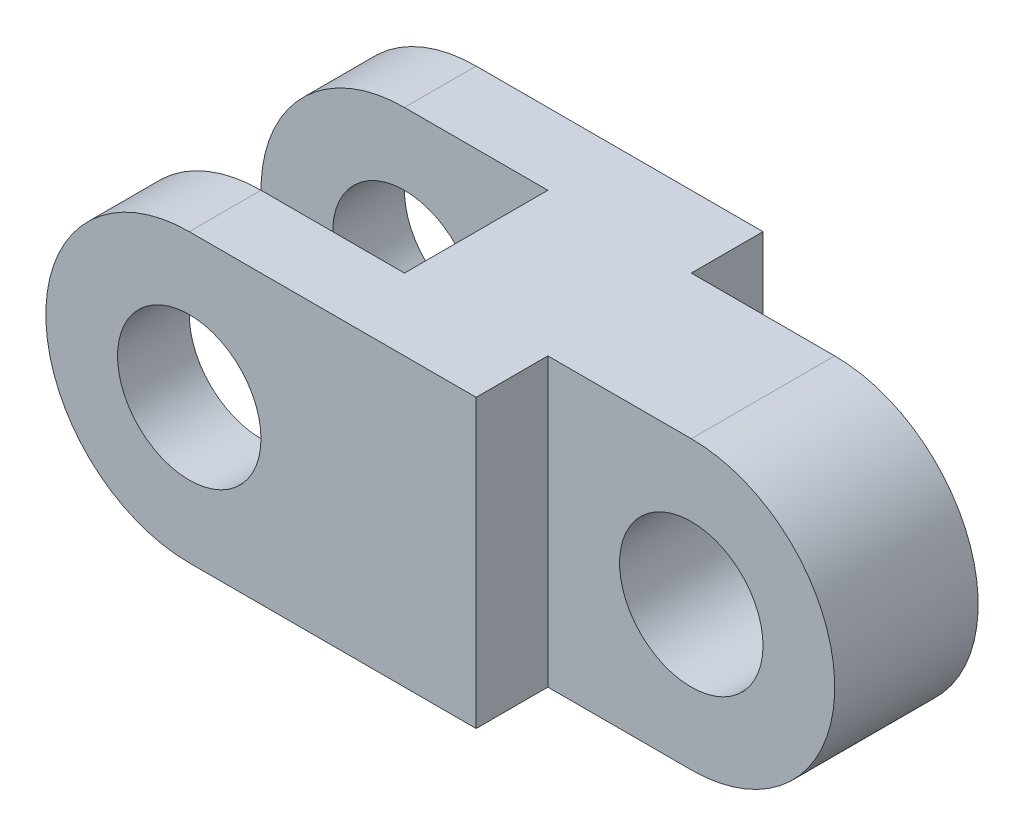
SolidWorks part; units mm, degrees
ref_plane "Front Plane" through (0, 0, 0) normal (0, 0, 1) x (1, 0, 0)
ref_plane "Top Plane" through (0, 0, 0) normal (0, 1, 0) x (1, 0, 0)
ref_plane "Right Plane" through (0, 0, 0) normal (1, 0, 0) x (0, 0, -1)
sketch "Sketch2" plane through (0, 0, 0) normal (0, 0, 1) x (1, 0, 0)
  line L1 (-75, -50) -> (75, -50)
  line L2 (-75, -50) -> (-75, 50)
  line L3 (-75, 50) -> (75, 50)
  line L4 (75, -50) -> (75, 50)
  line L5 (-75, -50) -> (75, 50) construction
  line L6 (-75, 50) -> (75, -50) construction
  circle A2 centre (-75, 0) radius 50
  circle A3 centre (75, 0) radius 50
  point P0 (0, 0)
  dimension "D1" = 150
  dimension "D2" = 100
extrude "Boss-Extrude1" add sketch "Sketch2" along normal mid plane 100 contours L2 A2 | L2 A2 | A3 L3 A2 L1 | L4 A3 | L4 A3
sketch "Sketch4" plane through (0, 0, 0) normal (0, 0, 1) x (1, 0, 0)
  line L0 (-75, -50) -> (-75, 50)
  line L2 (-75, -50) -> (75, -50)
  line L3 (75, 50) -> (-75, 50)
  line L4 (-75, -50) -> (75, -50)
  line L5 (75, 50) -> (-75, 50)
  arc A2 (-75, 50) -> (-75, -50) centre (-75, 0) ccw
  arc A3 (75, -50) -> (75, 50) centre (75, 0) ccw
  arc A4 (-75, 50) -> (-75, -50) centre (-75, 0) ccw
  arc A5 (75, -50) -> (75, 50) centre (75, 0) ccw
  point P8 (-75, 0)
  dimension "D1" = 0
extrude "Cut-Extrude1" cut sketch "Sketch4" against normal mid plane 50 contours L0 A4
sketch "Sketch7" plane through (0, 50, 0) normal (0, 1, 0) x (1, 0, 0)
  line L0 (-75, 25) -> (-25, 25)
  line L1 (-25, 25) -> (-25, -25)
  line L2 (-25, -25) -> (-75, -25)
  line L6 (75, 50) -> (-75, 50)
  line L7 (-75, 50) -> (-75, 25)
  line L8 (-75, 25) -> (-75, -25)
  line L9 (-75, -25) -> (-75, -50)
  line L10 (-75, -50) -> (75, -50)
  line L11 (75, -50) -> (75, 50)
  line L12 (75, 50) -> (-75, 50)
  line L13 (-75, 50) -> (-75, 25)
  line L14 (-75, 25) -> (-75, -25)
  line L15 (-75, -25) -> (-75, -50)
  line L16 (-75, -50) -> (75, -50)
  line L17 (75, -50) -> (75, 50)
  line M9 (-75, 25) -> (-75, -25)
  dimension "D2" = 25
  dimension "D1" = 0
extrude "Cut-Extrude2" cut sketch "Sketch7" against normal through all contours L2 L1 L0 M9
sketch "Sketch8" plane through (0, 0, 50) normal (0, 0, 1) x (1, 0, 0)
  line L2 (-75, -50) -> (75, -50)
  line L3 (75, 50) -> (-75, 50)
  line L4 (-75, -50) -> (75, -50)
  line L5 (75, 50) -> (-75, 50)
  circle A0 centre (-75, 0) radius 25
  arc A2 (-75, 50) -> (-75, -50) centre (-75, 0) ccw
  arc A3 (75, -50) -> (75, 50) centre (75, 0) ccw
  arc A4 (-75, 50) -> (-75, -50) centre (-75, 0) ccw
  arc A5 (75, -50) -> (75, 50) centre (75, 0) ccw
  dimension "D2" = 50
  dimension "D1" = 0
extrude "Cut-Extrude3" cut sketch "Sketch8" against normal through all both and the other way through all contours A0
sketch "Sketch9" plane through (0, 0, 50) normal (0, 0, 1) x (1, 0, 0)
  line L2 (-75, -50) -> (75, -50)
  line L3 (75, 50) -> (-75, 50)
  line L4 (-75, -50) -> (75, -50)
  line L5 (75, 50) -> (-75, 50)
  circle A0 centre (75, 0) radius 25
  arc A2 (-75, 50) -> (-75, -50) centre (-75, 0) ccw
  arc A3 (75, -50) -> (75, 50) centre (75, 0) ccw
  arc A4 (-75, 50) -> (-75, -50) centre (-75, 0) ccw
  arc A5 (75, -50) -> (75, 50) centre (75, 0) ccw
  dimension "D2" = 50
  dimension "D1" = 0
extrude "Cut-Extrude4" cut sketch "Sketch9" against normal through all both contours A0
sketch "Sketch13" plane through (0, 0, 50) normal (0, 0, 1) x (1, 0, 0)
  line L0 (25, 50) -> (25, -50)
  line L1 (-75, 50) -> (75, 50) construction
  line L2 (-75, -50) -> (75, -50) construction
  dimension "D1" = 25
sketch "Sketch15" plane through (0, 0, 50) normal (0, 0, 1) x (1, 0, 0)
  line L0 (25, 50) -> (25, -50) construction
  line L1 (25, 50) -> (25, -50)
  line L2 (-75, -50) -> (75, -50)
  line L3 (75, 50) -> (-75, 50)
  line L4 (-75, -50) -> (75, -50)
  line L5 (75, 50) -> (-75, 50)
  arc A2 (-75, 50) -> (-75, -50) centre (-75, 0) ccw
  arc A3 (75, -50) -> (75, 50) centre (75, 0) ccw
  arc A4 (-75, 50) -> (-75, -50) centre (-75, 0) ccw
  arc A5 (75, -50) -> (75, 50) centre (75, 0) ccw
  circle M5 centre (75, 0) radius 25
  line M8 (-75, -50) -> (75, -50)
  arc M9 (75, -50) -> (75, 50) centre (75, 0) ccw
  line M10 (75, 50) -> (-75, 50)
  dimension "D1" = 0
extrude "Cut-Extrude5" cut sketch "Sketch15" against normal blind 25 contours L1 M10 M8 M9 M5
mirror "Mirror1" about plane through (0, 0, 0) normal (0, 0, 1) of "Cut-Extrude5"
